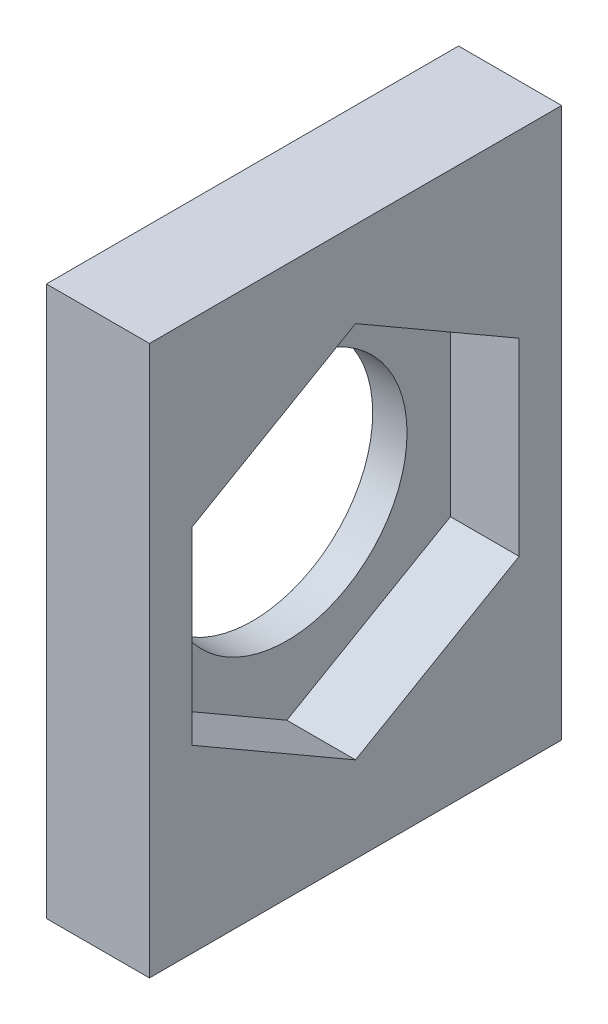
SolidWorks part; units mm, degrees
ref_plane "Front Plane" through (0, 0, 0) normal (0, 0, 1) x (1, 0, 0)
ref_plane "Top Plane" through (0, 0, 0) normal (0, 1, 0) x (1, 0, 0)
ref_plane "Right Plane" through (0, 0, 0) normal (1, 0, 0) x (0, 0, -1)
sketch "Sketch1" plane through (0, 0, 0) normal (1, 0, 0) x (0, 0, -1)
  line L1 (0, 0) -> (12, 0)
  line L2 (0, 0) -> (0, 12)
  line L3 (0, 12) -> (12, 12)
  line L4 (12, 0) -> (12, 12)
  dimension "D1" = 12
  dimension "D2" = 12
extrude "Boss-Extrude1" add sketch "Sketch1" along normal blind 3
sketch "Sketch2" plane through (3, 0, 0) normal (1, 0, 0) x (0, 0, -1)
  circle A0 centre (6, 6) radius 3.5
  dimension "D1" = 7
extrude "Cut-Extrude1" cut sketch "Sketch2" against normal blind 3
sketch "Sketch3" plane through (3, 0, 0) normal (1, 0, 0) x (0, 0, -1)
  line L1 (6, 11.5) -> (1.2369, 8.75)
  line L2 (1.2369, 8.75) -> (1.2369, 3.25)
  line L3 (1.2369, 3.25) -> (6, 0.5)
  line L4 (6, 0.5) -> (10.7631, 3.25)
  line L5 (10.7631, 3.25) -> (10.7631, 8.75)
  line L6 (10.7631, 8.75) -> (6, 11.5)
  circle A0 centre (6, 6) radius 4.7631 construction
  dimension "D1" = 5.5
extrude "Cut-Extrude2" cut sketch "Sketch3" against normal blind 2
sketch "Sketch4" plane through (0, 12, 0) normal (0, 1, 0) x (1, 0, 0)
  line L1 (0, 0) -> (3, 0)
  line L2 (0, 0) -> (0, 12)
  line L3 (0, 12) -> (3, 12)
  line L4 (3, 0) -> (3, 12)
extrude "Boss-Extrude2" add sketch "Sketch4" along normal blind 2
sketch "Sketch5" plane through (0, 0, 0) normal (0, -1, 0) x (1, 0, 0)
  line L1 (3, -12) -> (0, -12)
  line L2 (3, -12) -> (3, 0)
  line L3 (3, 0) -> (0, 0)
  line L4 (0, -12) -> (0, 0)
extrude "Boss-Extrude3" add sketch "Sketch5" along normal blind 2
